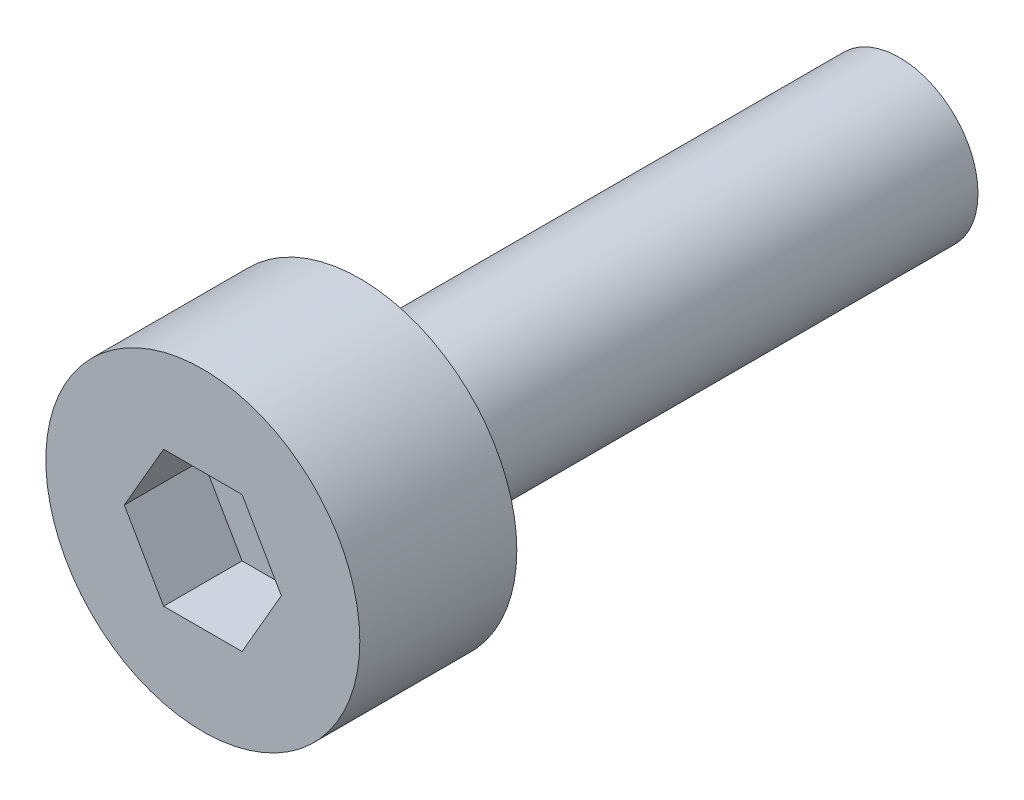
SolidWorks part; units mm, degrees
ref_plane "前视基准面" through (0, 0, 0) normal (0, 0, 1) x (1, 0, 0)
ref_plane "上视基准面" through (0, 0, 0) normal (0, 1, 0) x (1, 0, 0)
ref_plane "右视基准面" through (0, 0, 0) normal (1, 0, 0) x (0, 0, -1)
sketch "草图1" plane through (0, 0, 0) normal (0, 0, 1) x (1, 0, 0)
  circle A0 centre (0, 0) radius 1.6
extrude "凸台-拉伸1" add sketch "草图1" along normal blind 1.6
sketch "草图3" plane through (0, 0, 0) normal (0, 0, 1) x (1, 0, 0)
  circle A0 centre (0, 0) radius 0.8
extrude "凸台-拉伸3" add sketch "草图3" against normal blind 5.5 contours A0
sketch "草图4" plane through (0, 0, 1.6) normal (0, 0, 1) x (1, 0, 0)
  line L1 (0.8, 0) -> (0.4, 0.6928)
  line L2 (0.4, 0.6928) -> (-0.4, 0.6928)
  line L3 (-0.4, 0.6928) -> (-0.8, 0)
  line L4 (-0.8, 0) -> (-0.4, -0.6928)
  line L5 (-0.4, -0.6928) -> (0.4, -0.6928)
  line L6 (0.4, -0.6928) -> (0.8, 0)
  circle A0 centre (0, 0) radius 0.8 construction
extrude "切除-拉伸1" cut sketch "草图4" against normal blind 0.8
